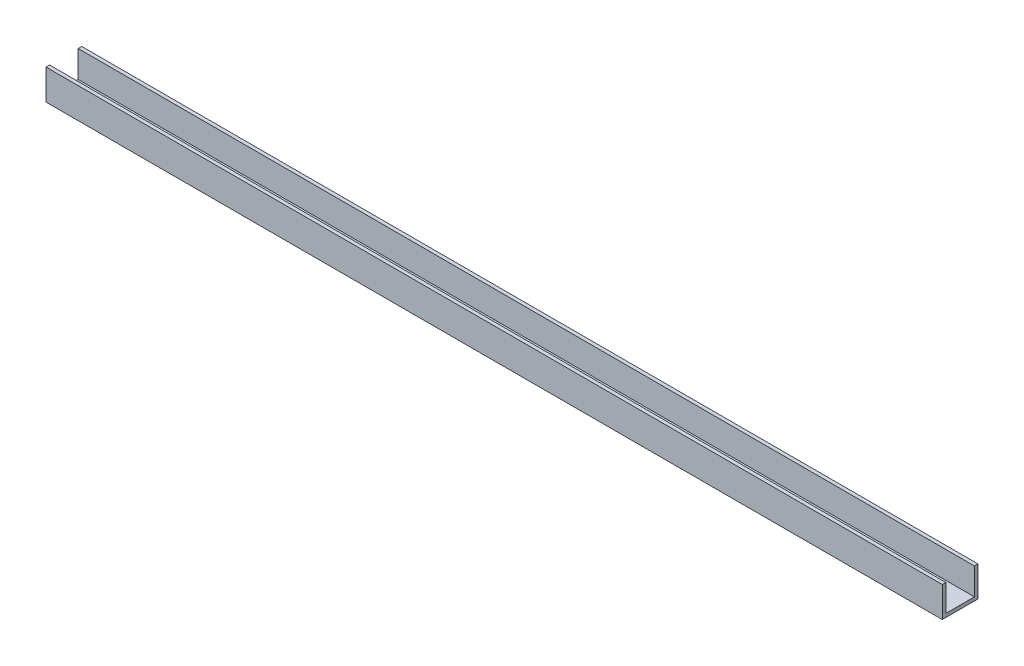
SolidWorks part; units mm, degrees
ref_plane "Plan de face" through (0, 0, 0) normal (0, 0, 1) x (1, 0, 0)
ref_plane "Plan de dessus" through (0, 0, 0) normal (0, 1, 0) x (1, 0, 0)
ref_plane "Plan de droite" through (0, 0, 0) normal (1, 0, 0) x (0, 0, -1)
sketch "Sketch2" plane through (0, 0, 0) normal (1, 0, 0) x (0, 0, -1)
  line L0 (-4, 4.25) -> (-4, -3.25)
  line L1 (5, -4.25) -> (-5, -4.25)
  line L2 (5, -4.25) -> (5, 4.25)
  line L3 (5, 4.25) -> (4, 4.25)
  line L4 (-5, -4.25) -> (-5, 4.25)
  line L5 (5, -4.25) -> (3.8235, -3.25) construction
  line L7 (-4, -3.25) -> (4, -3.25)
  line L8 (4, -3.25) -> (4, 4.25)
  line L9 (-4, 4.25) -> (-5, 4.25)
  line L11 (-3.8235, -3.25) -> (-5, -4.25) construction
  point P0 (0, 0)
  dimension "D1" = 8.5
  dimension "D2" = 10
  dimension "D3" = 1
  dimension "D4" = 1
  dimension "D5" = 1
extrude "Boss-Extrude1" add sketch "Sketch2" along normal blind 251
sketch "Sketch3" plane through (0, -4.25, 0) normal (0, -1, 0) x (1, 0, 0)
  line L0 (251, 5) -> (251, -5) construction
  circle A0 centre (19, 0) radius 2.5
  circle A1 centre (27.5, 0) radius 2.5
  circle A2 centre (36, 0) radius 2.5
  circle A3 centre (115, 0) radius 2.5
  circle A4 centre (123.5, 0) radius 2.5
  circle A5 centre (132, 0) radius 2.5
  circle A6 centre (232, 0) radius 2.5
  circle A7 centre (223.5, 0) radius 2.5
  circle A8 centre (215, 0) radius 2.5
  dimension "D1" = 19
  dimension "D2" = 8.5
  dimension "D3" = 8.5
  dimension "D4" = 115
  dimension "D5" = 8.5
  dimension "D6" = 8.5
  dimension "D7" = 19
  dimension "D8" = 8.5
  dimension "D9" = 8.5
extrude "Cut-Extrude1" cut sketch "Sketch3" against normal up to next
